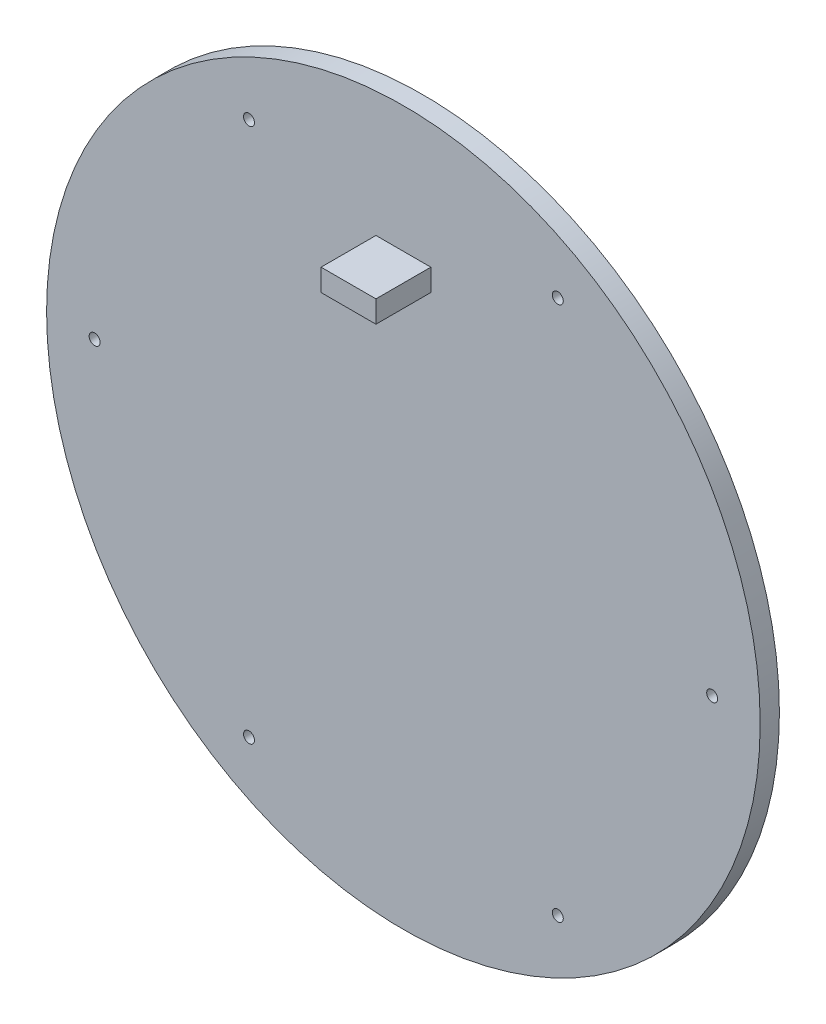
SolidWorks part; units mm, degrees
ref_plane "前视基准面" through (0, 0, 0) normal (0, 0, 1) x (1, 0, 0)
ref_plane "上视基准面" through (0, 0, 0) normal (0, 1, 0) x (1, 0, 0)
ref_plane "右视基准面" through (0, 0, 0) normal (1, 0, 0) x (0, 0, -1)
other "Configuration Table"
sketch "草图1" plane through (0, 0, 0) normal (0, 0, 1) x (1, 0, 0)
  circle A0 centre (0, 0) radius 65
  dimension "D1" = 130
extrude "凸台-拉伸1" add sketch "草图1" along normal blind 3.5
sketch "草图2" plane through (0, 0, 3.5) normal (0, 0, 1) x (1, 0, 0)
  line L1 (-5, 38) -> (5, 38)
  line L2 (-5, 38) -> (-5, 42)
  line L3 (-5, 42) -> (5, 42)
  line L4 (5, 38) -> (5, 42)
  line L5 (-5, 38) -> (5, 42) construction
  line L6 (-5, 42) -> (5, 38) construction
  point P0 (0, 40)
  dimension "D1" = 40
  dimension "D2" = 10
  dimension "D3" = 4
extrude "凸台-拉伸2" add sketch "草图2" along normal mid plane 20
sketch "草图3" plane through (0, 0, 0) normal (0, 0, -1) x (-1, 0, 0)
  circle A0 centre (0, 0) radius 56.25 construction
  circle A1 centre (56.25, 0) radius 1
  circle A2 centre (28.125, -48.7139) radius 1
  circle A3 centre (-28.125, -48.7139) radius 1
  circle A4 centre (-56.25, 0) radius 1
  circle A5 centre (-28.125, 48.7139) radius 1
  circle A6 centre (28.125, 48.7139) radius 1
  point P17 (0, 0)
  dimension "D1" = 2
  dimension "D2" = 112.5
  dimension "D3" = 6
extrude "切除-拉伸1" cut sketch "草图3" against normal blind 10
